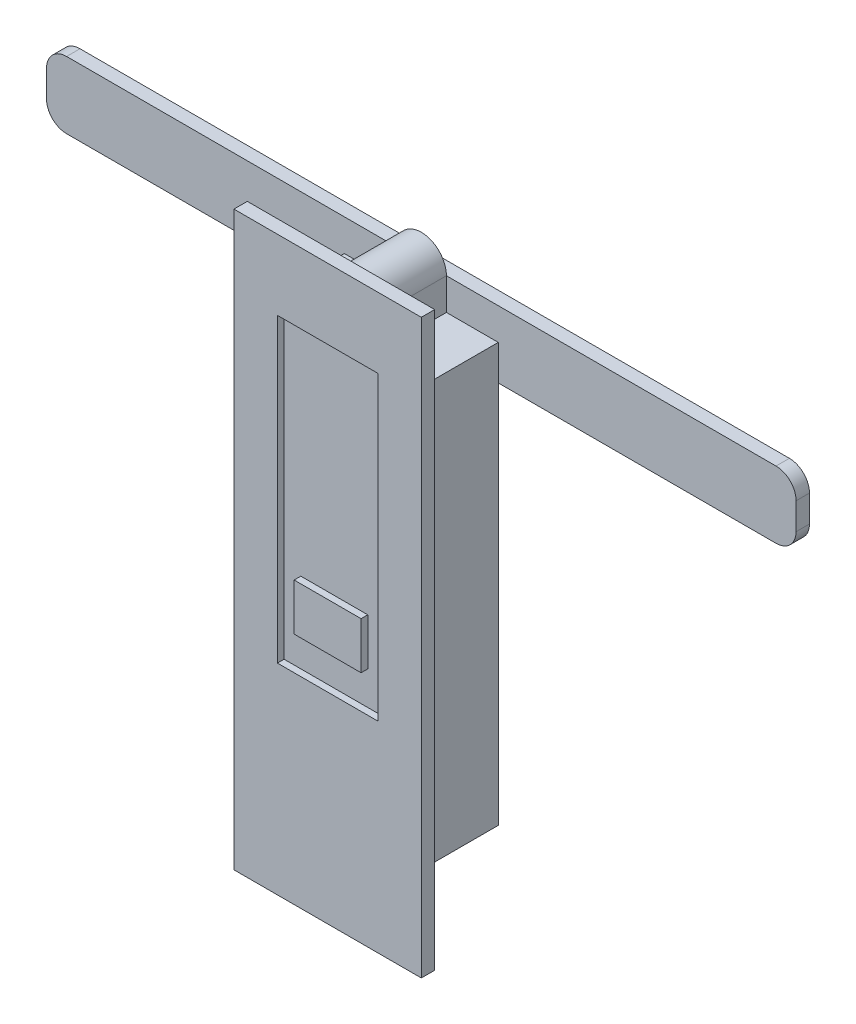
SolidWorks part; units mm, degrees
ref_plane "前视基准面" through (0, 0, 0) normal (0, 0, 1) x (1, 0, 0)
ref_plane "上视基准面" through (0, 0, 0) normal (0, 1, 0) x (1, 0, 0)
ref_plane "右视基准面" through (0, 0, 0) normal (1, 0, 0) x (0, 0, -1)
sketch "草图1" plane through (0, 0, 0) normal (0, 0, 1) x (1, 0, 0)
  line L1 (-14, -42.75) -> (14, -42.75)
  line L2 (-14, -42.75) -> (-14, 42.75)
  line L3 (-14, 42.75) -> (14, 42.75)
  line L4 (14, -42.75) -> (14, 42.75)
  line L5 (-14, -42.75) -> (14, 42.75) construction
  line L6 (-14, 42.75) -> (14, -42.75) construction
  point P0 (0, 0)
  dimension "D1" = 28
  dimension "D2" = 85.5
extrude "凸台-拉伸1" add sketch "草图1" along normal blind 2
sketch "草图2" plane through (0, 0, 2) normal (0, 0, 1) x (1, 0, 0)
  line L0 (0, 42.75) -> (0, -42.75) construction
  line L1 (14, 42.75) -> (-14, 42.75) construction
  line L2 (-14, -42.75) -> (14, -42.75) construction
  line L4 (-7.5, -12.75) -> (7.5, -12.75)
  line L5 (-7.5, -12.75) -> (-7.5, 32.25)
  line L6 (-7.5, 32.25) -> (7.5, 32.25)
  line L7 (7.5, -12.75) -> (7.5, 32.25)
  line L8 (-7.5, -12.75) -> (7.5, 32.25) construction
  line L9 (-7.5, 32.25) -> (7.5, -12.75) construction
  line L10 (-5, -7.75) -> (5, -7.75)
  line L11 (-5, -7.75) -> (-5, -0.75)
  line L12 (-5, -0.75) -> (5, -0.75)
  line L13 (5, -7.75) -> (5, -0.75)
  line L14 (-5, -7.75) -> (5, -0.75) construction
  line L15 (-5, -0.75) -> (5, -7.75) construction
  point P6 (0, 9.75)
  point P12 (0, -4.25)
  dimension "D1" = 15
  dimension "D2" = 45
  dimension "D3" = 30
  dimension "D4" = 10
  dimension "D5" = 7
  dimension "D6" = 5
extrude "切除-拉伸1" cut sketch "草图2" against normal blind 1
sketch "草图3" plane through (0, 0, 0) normal (0, 0, -1) x (-1, 0, 0)
  line L0 (0, 42.75) -> (0, -42.75) construction
  line L1 (-14, 42.75) -> (14, 42.75) construction
  line L2 (14, -42.75) -> (-14, -42.75) construction
  line L3 (0, -36) -> (0, 36) construction
  line L4 (-11.5, -31.25) -> (11.5, -31.25)
  line L5 (-11.5, -31.25) -> (-11.5, 31.25)
  line L6 (-11.5, 31.25) -> (11.5, 31.25)
  line L7 (11.5, -31.25) -> (11.5, 31.25)
  line L8 (-11.5, -31.25) -> (11.5, 31.25) construction
  line L9 (-11.5, 31.25) -> (11.5, -31.25) construction
  line L10 (-3.75, -36) -> (-3.75, 36)
  line L11 (3.75, -36) -> (3.75, 36)
  arc A0 (-3.75, -36) -> (3.75, -36) centre (0, -36) ccw
  arc A1 (3.75, 36) -> (-3.75, 36) centre (0, 36) ccw
  point P6 (0, 0)
  point P14 (0, 0)
  dimension "D1" = 23
  dimension "D2" = 62.5
  dimension "D3" = 7.5
  dimension "D4" = 72
extrude "凸台-拉伸2" add sketch "草图3" along normal blind 12 contours L4 L11 L6 L10 | L4 L10 L6 L5 | L11 L4 L7 L6 | L11 A1 L10 L6 | L10 A0 L11 L4
sketch "草图4" plane through (0, 0, -12) normal (0, 0, -1) x (-1, 0, 0)
  line L0 (0, 36) -> (53, 36)
  line L1 (56, 33) -> (56, 29)
  line L2 (53, 26) -> (0, 26)
  line L3 (0, 26) -> (0, 36)
  arc A0 (56, 29) -> (53, 26) centre (53, 29) cw
  arc A1 (56, 33) -> (53, 36) centre (53, 33) ccw
  point P7 (56, 26)
  point P10 (56, 36)
  dimension "D3" = 3
  dimension "D1" = 56
  dimension "D2" = 10
extrude "凸台-拉伸3" add sketch "草图4" along normal blind 2 separate body
mirror "镜向2" about plane through (0, 0, 0) normal (1, 0, 0) of bodies 109
